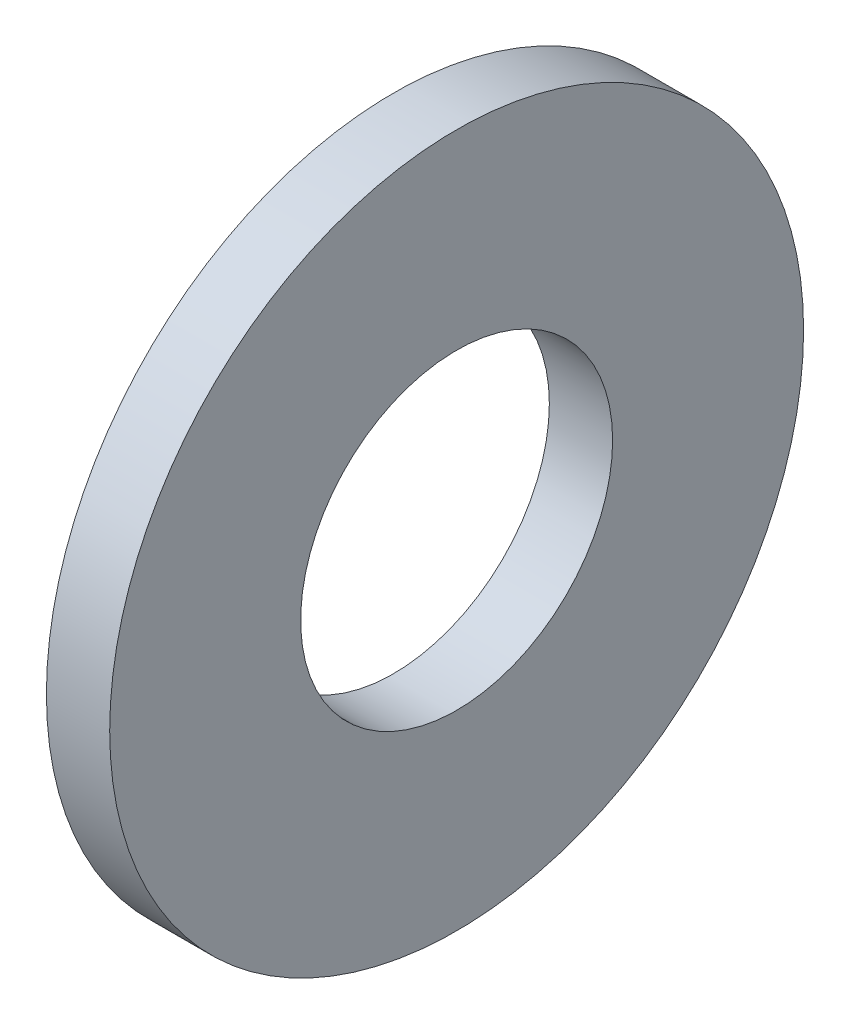
SolidWorks part; units mm, degrees
ref_plane "Front Plane" through (0, 0, 0) normal (0, 0, 1) x (1, 0, 0)
ref_plane "Top Plane" through (0, 0, 0) normal (0, 1, 0) x (1, 0, 0)
ref_plane "Right Plane" through (0, 0, 0) normal (1, 0, 0) x (0, 0, -1)
sketch "Sketch1" plane through (0, 0, 0) normal (1, 0, 0) x (0, 0, -1)
  circle A0 centre (0, 0) radius 3.5687
  circle A1 centre (0, 0) radius 7.9375
  dimension "D1" = 7.1374
  dimension "D2" = 15.875
extrude "Boss-Extrude1" add sketch "Sketch1" along normal blind 1.4478
